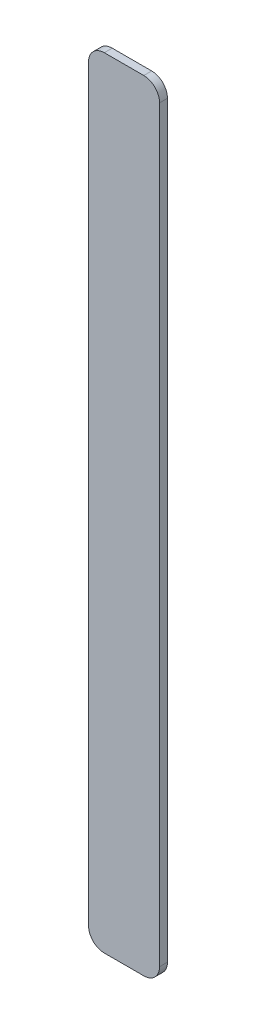
SolidWorks part; units mm, degrees
ref_plane "Front Plane" through (0, 0, 0) normal (0, 0, 1) x (1, 0, 0)
ref_plane "Top Plane" through (0, 0, 0) normal (0, 1, 0) x (1, 0, 0)
ref_plane "Right Plane" through (0, 0, 0) normal (1, 0, 0) x (0, 0, -1)
sketch "Sketch1" plane through (0, 0, 0) normal (0, 0, 1) x (1, 0, 0)
  line L0 (-2.5, -1) -> (0, -1)
  line L1 (1, 0) -> (1, 47.4)
  line L2 (0, 48.4) -> (-2.5, 48.4)
  line L3 (-3.5, 47.4) -> (-3.5, 0)
  arc A0 (-3.5, 0) -> (-2.5, -1) centre (-2.5, 0) ccw
  arc A1 (0, -1) -> (1, 0) centre (0, 0) ccw
  arc A2 (1, 47.4) -> (0, 48.4) centre (0, 47.4) ccw
  arc A3 (-2.5, 48.4) -> (-3.5, 47.4) centre (-2.5, 47.4) ccw
  point P12 (1.2548, -22.5176)
  point P13 (0, 0)
  dimension "D3" = 1
  dimension "D1" = 49.4
  dimension "D2" = 4.5
extrude "Boss-Extrude1" add sketch "Sketch1" along normal blind 0.5
